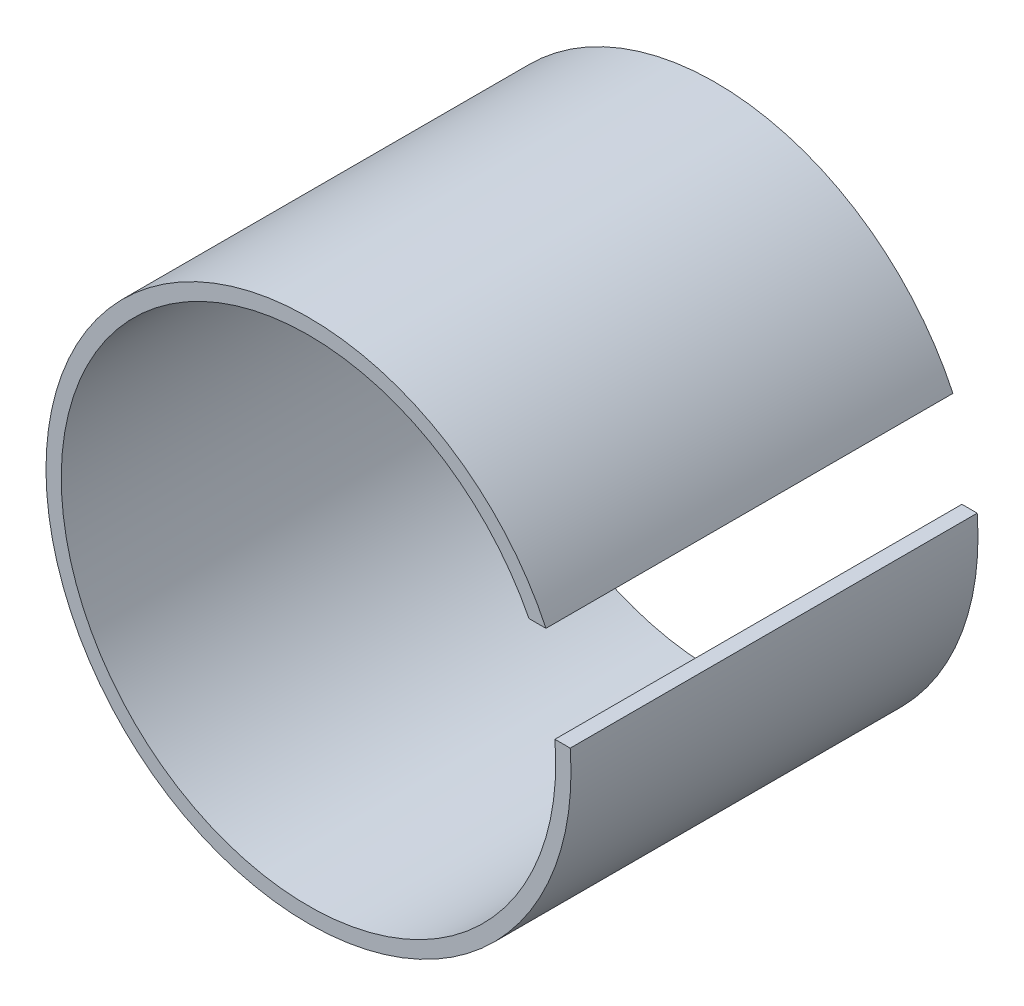
SolidWorks part; units mm, degrees
ref_plane "Спереди" through (0, 0, 0) normal (0, 0, 1) x (1, 0, 0)
ref_plane "Сверху" through (0, 0, 0) normal (0, 1, 0) x (1, 0, 0)
ref_plane "Справа" through (0, 0, 0) normal (1, 0, 0) x (0, 0, -1)
sketch "Эскиз1" plane through (0, 0, 0) normal (0, 0, 1) x (1, 0, 0)
  line L0 (0, 0) -> (35.0509, 0) construction
  line L2 (0, 0) -> (0, 32.4467)
  line L3 (21.6677, 11) -> (23.3375, 11)
  line L4 (24.2176, 2) -> (25.7224, 2)
  arc A0 (21.6677, 11) -> (24.2176, 2) centre (0, 0) ccw
  arc A2 (23.3375, 11) -> (25.7224, 2) centre (0, 0) ccw
  circle A4 centre (0, 0) radius 24.3 construction
  circle A5 centre (0, 0) radius 25.8 construction
  point P1 (26.3, 0)
  point P8 (0, 24.3)
  point P14 (23.2382, 7.1046)
  dimension "D1" = 48.6
  dimension "D2" = 1.5
extrude "Бобышка-Вытянуть1" add sketch "Эскиз1" along normal blind 40 contours L3 A2 L2 A0 | L2 A2 L4 A0
